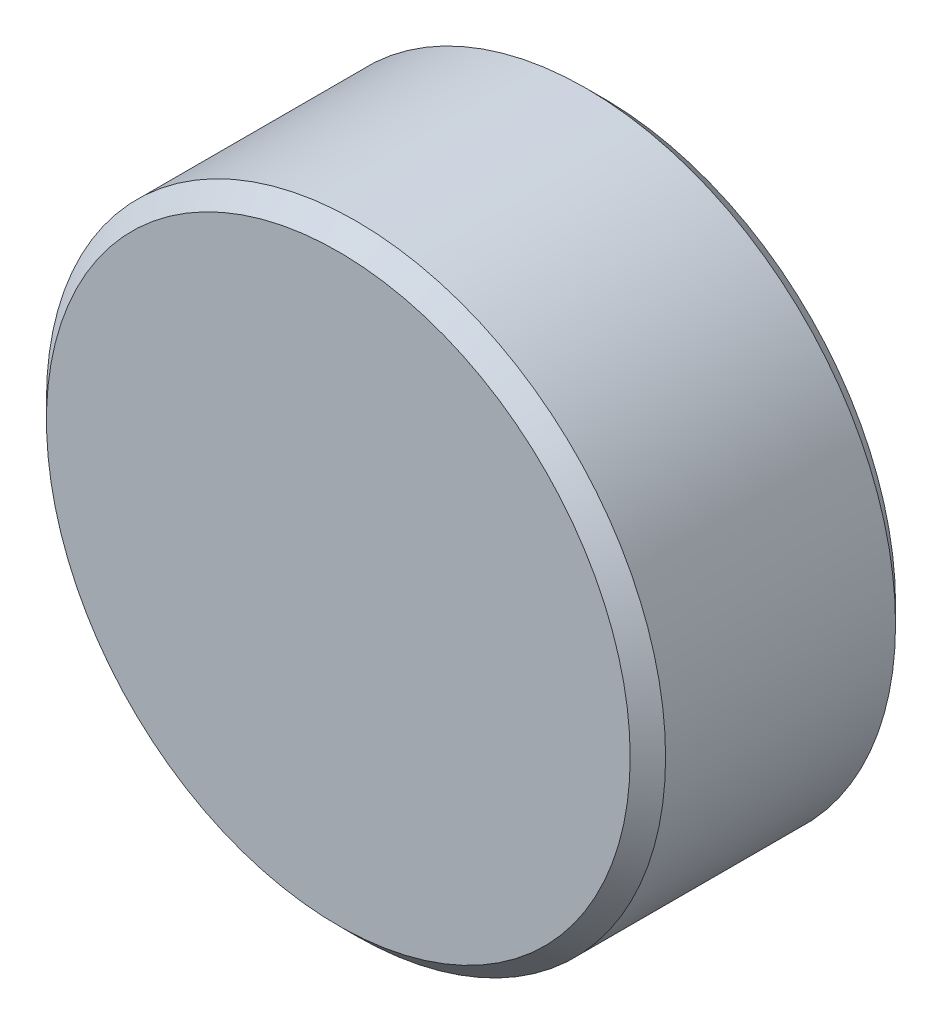
SolidWorks part; units mm, degrees
ref_plane "Plan de face" through (0, 0, 0) normal (0, 0, 1) x (1, 0, 0)
ref_plane "Plan de dessus" through (0, 0, 0) normal (0, 1, 0) x (1, 0, 0)
ref_plane "Plan de droite" through (0, 0, 0) normal (1, 0, 0) x (0, 0, -1)
sketch "Esquisse1" plane through (0, 0, 0) normal (0, 0, 1) x (1, 0, 0)
  circle A0 centre (0, 0) radius 35
extrude "Extrusion1" add sketch "Esquisse1" along normal blind 30
chamfer "Chanfrein1" distance 2 angle 45 1 edges at (35, 0, 30)
chamfer "Chanfrein2" distance 2 angle 45 1 edges at (35, 0, 0)
